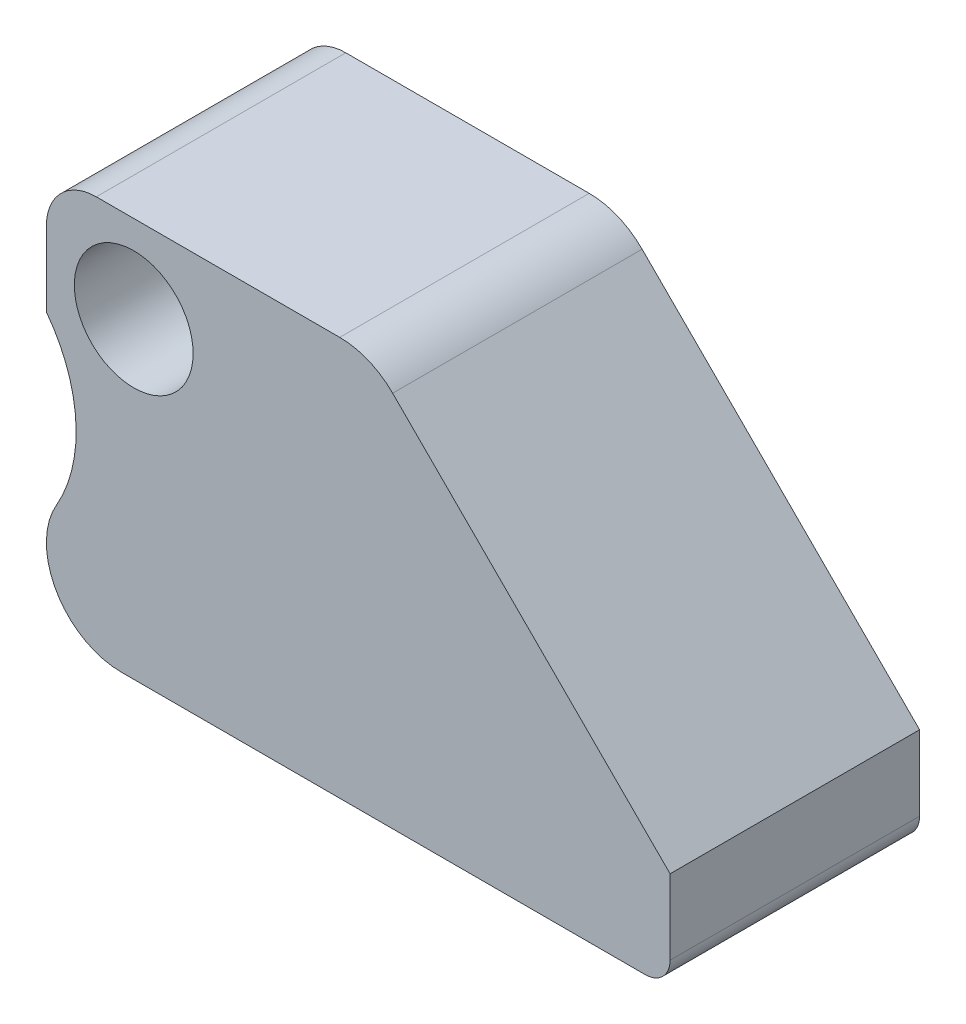
SolidWorks part; units mm, degrees
material "AISI 4130 Steel, normalized at 870C"
ref_plane "Front Plane" through (0, 0, 0) normal (0, 0, 1) x (1, 0, 0)
ref_plane "Top Plane" through (0, 0, 0) normal (0, 1, 0) x (1, 0, 0)
ref_plane "Right Plane" through (0, 0, 0) normal (1, 0, 0) x (0, 0, -1)
sketch "Sketch1" plane through (0, 0, 0) normal (0, 0, 1) x (1, 0, 0)
  line L0 (0.5, 8) -> (12.5, -4)
  line L1 (12.5, -8) -> (-12.5, -8)
  line L2 (12.5, -8) -> (12.5, 8)
  line L3 (12.5, 8) -> (-12.5, 8)
  line L4 (-12.5, -8) -> (-12.5, 8)
  line L5 (12.5, -8) -> (-12.5, 8) construction
  line L6 (12.5, 8) -> (-12.5, -8) construction
  circle A0 centre (-9, 4.5) radius 2.3813
  arc A1 (-12.5, -5) -> (-9.5, -8) centre (-9.5, -5) ccw
  arc A2 (-12.5, -5) -> (-12.0981, -3.5) centre (-9.5, -5) cw
  arc A3 (-12.0981, -3.5) -> (-12.5, 3) centre (-17.2021, -0.5532) ccw
  point P0 (0, 0)
  point P16 (-12.0685, -3.45)
  point P17 (-12.5, 3.0205)
  dimension "D3" = 4.7625
  dimension "D1" = 25
  dimension "D2" = 16
  dimension "D4" = 3.5
  dimension "D5" = 3.5
  dimension "D6" = 12
  dimension "D7" = 12
  dimension "D8" = 5
  dimension "D9" = 3
  dimension "D10" = 1.5
extrude "Boss-Extrude1" add sketch "Sketch1" along normal blind 10 contours L4 L1 L2 L0 L3 A0
fillet "Fillet5" radius 3 1 edges at (0.5, 8, 5)
fillet "Fillet6" radius 1 1 edges at (12.5, -8, 5)
fillet "Fillet7" radius 2 1 edges at (-12.5, 8, 5)
